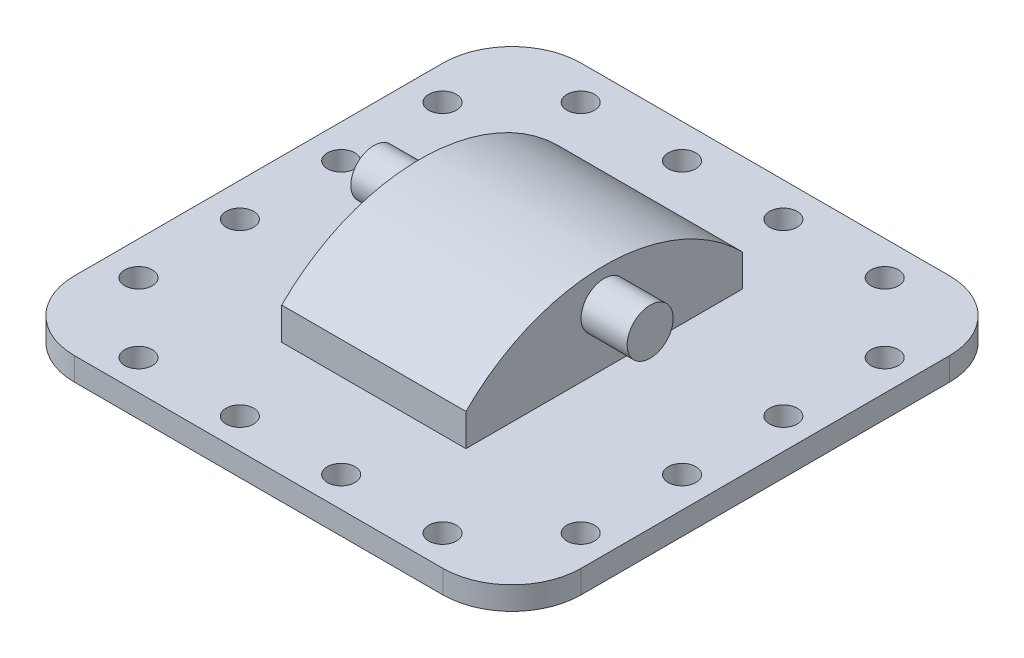
SolidWorks part; units mm, degrees
ref_plane "Front Plane" through (0, 0, 0) normal (0, 0, 1) x (1, 0, 0)
ref_plane "Top Plane" through (0, 0, 0) normal (0, 1, 0) x (1, 0, 0)
ref_plane "Right Plane" through (0, 0, 0) normal (1, 0, 0) x (0, 0, -1)
sketch "Sketch1" plane through (0, 0, 0) normal (0, 1, 0) x (1, 0, 0)
  line L1 (-55, -55) -> (55, -55)
  line L2 (-55, -55) -> (-55, 55)
  line L3 (-55, 55) -> (55, 55)
  line L4 (55, -55) -> (55, 55)
  line L5 (-55, -55) -> (55, 55) construction
  line L6 (-55, 55) -> (55, -55) construction
  point P0 (0, 0)
  dimension "D1" = 110
  dimension "D2" = 110
extrude "Boss-Extrude1" add sketch "Sketch1" along normal blind 5
fillet "Fillet2" radius 15 1 edges at (55, 2.5, -55)
fillet "Fillet3" radius 15 1 edges at (-55, 2.5, -55)
fillet "Fillet4" radius 15 1 edges at (-55, 2.5, 55)
fillet "Fillet5" radius 15 1 edges at (55, 2.5, 55)
sketch "Sketch2" plane through (0, 5, 0) normal (0, 1, 0) x (1, 0, 0)
  line L1 (-20, -30) -> (20, -30)
  line L2 (-20, -30) -> (-20, 30)
  line L3 (-20, 30) -> (20, 30)
  line L4 (20, -30) -> (20, 30)
  line L5 (-20, -30) -> (20, 30) construction
  line L6 (-20, 30) -> (20, -30) construction
  point P0 (0, 0)
  dimension "D1" = 40
extrude "Boss-Extrude2" add sketch "Sketch2" along normal blind 24
sketch "Sketch4" plane through (20, 0, 0) normal (1, 0, 0) x (0, 0, -1)
  line L0 (-30, 17) -> (30, 17) construction
  line L1 (-30, 29) -> (-30, 5) construction
  line L2 (30, 29) -> (30, 5) construction
  line L3 (0, 17) -> (0, 29) construction
  line L4 (-30, 29) -> (30, 29) construction
  line L5 (0, 29) -> (0, 5) construction
  line L6 (-40, 5) -> (40, 5) construction
  circle A2 centre (0, 17) radius 5
extrude "Boss-Extrude3" add sketch "Sketch4" along normal blind 10 and the other way blind 50
fillet "Fillet6" radius 10 1 edges at (0, 29, 30)
fillet "Fillet7" radius 10 1 edges at (0, 29, -30)
sketch "Sketch5" plane through (0, 0, 0) normal (0, -1, 0) x (1, 0, 0)
  line L0 (55.3347, -39.5816) -> (55.3347, 40.4184)
  line L1 (40.3347, 55.4184) -> (-39.6653, 55.4184)
  line L2 (-54.6653, 40.4184) -> (-54.6653, -39.5816)
  line L3 (-39.6653, -54.5816) -> (40.3347, -54.5816)
  circle A0 centre (48.3347, -10.5816) radius 3
  circle A1 centre (48.3347, 33.4184) radius 3
  circle A2 centre (-47.6653, 11.4184) radius 3
  circle A3 centre (-47.6653, -10.5816) radius 3
  circle A4 centre (-47.6653, -32.5816) radius 3
  circle A5 centre (-32.6653, -47.5816) radius 3
  circle A6 centre (-10.6653, -47.5816) radius 3
  circle A7 centre (11.3347, -47.5816) radius 3
  circle A8 centre (33.3347, -47.5816) radius 3
  circle A9 centre (48.3347, -32.5816) radius 3
  circle A10 centre (48.3347, 11.4184) radius 3
  circle A11 centre (33.3347, 48.4184) radius 3
  circle A12 centre (11.3347, 48.4184) radius 3
  circle A13 centre (-10.6653, 48.4184) radius 3
  circle A14 centre (-32.6653, 48.4184) radius 3
  circle A15 centre (-47.6653, 33.4184) radius 3
  arc A16 (55.3347, 40.4184) -> (40.3347, 55.4184) centre (40.3347, 40.4184) ccw
  arc A17 (-39.6653, 55.4184) -> (-54.6653, 40.4184) centre (-39.6653, 40.4184) ccw
  arc A18 (-54.6653, -39.5816) -> (-39.6653, -54.5816) centre (-39.6653, -39.5816) ccw
  arc A19 (40.3347, -54.5816) -> (55.3347, -39.5816) centre (40.3347, -39.5816) ccw
extrude "Cut-Extrude1" cut sketch "Sketch5" against normal blind 10 contours A1 | A0 | A5 | A4 | A3 | A2 | A13 | A12 | A11 | A10 | A9 | A8 | A7 | A6 | A15 | A14
sketch "Sketch6" plane through (20, 0, 0) normal (1, 0, 0) x (0, 0, -1)
  line L0 (-30, 19) -> (-30, 5) construction
  line L1 (30, 19) -> (30, 5) construction
  line L2 (-20, 29) -> (20, 29) construction
  line L3 (30, 19) -> (30, 12)
  line L4 (-20, 29) -> (20, 29)
  line L5 (-30, 19) -> (-30, 12)
  arc A0 (-30, 12) -> (30, 12) centre (0, -18) cw
  arc A1 (30, 19) -> (20, 29) centre (20, 19) ccw construction
  arc A2 (-20, 29) -> (-30, 19) centre (-20, 19) ccw construction
  arc A3 (30, 19) -> (20, 29) centre (20, 19) ccw
  arc A4 (-20, 29) -> (-30, 19) centre (-20, 19) ccw
extrude "Cut-Extrude2" cut sketch "Sketch6" against normal blind 60
